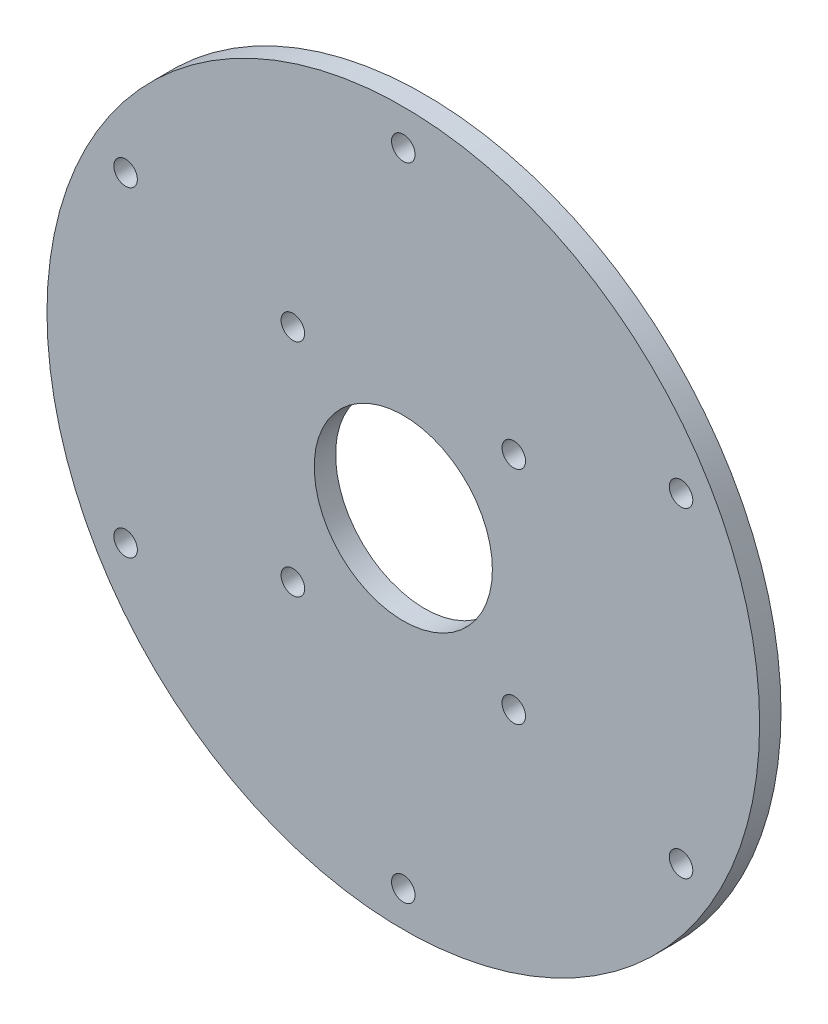
SolidWorks part; units mm, degrees
ref_plane "前视基准面" through (0, 0, 0) normal (0, 0, 1) x (1, 0, 0)
ref_plane "上视基准面" through (0, 0, 0) normal (0, 1, 0) x (1, 0, 0)
ref_plane "右视基准面" through (0, 0, 0) normal (1, 0, 0) x (0, 0, -1)
other "Configuration Table"
sketch "草图1" plane through (0, 0, 0) normal (0, 0, 1) x (1, 0, 0)
  line L0 (0, 0) -> (61.0193, 0) construction
  line L1 (0, 40) -> (0, -27.3482) construction
  line L2 (-38.9711, 22.5) -> (0, 0) construction
  circle A0 centre (0, 0) radius 50
  circle A1 centre (-15.5, 15.5) radius 1.65
  circle A2 centre (15.5, 15.5) radius 1.65
  circle A3 centre (15.5, -15.5) radius 1.65
  circle A4 centre (-15.5, -15.5) radius 1.65
  circle A5 centre (0, 0) radius 12.5
  circle A6 centre (-38.9711, 22.5) radius 1.65
  circle A12 centre (0, 45) radius 1.65
  circle A13 centre (38.9711, 22.5) radius 1.65
  circle A14 centre (38.9711, -22.5) radius 1.65
  circle A15 centre (0, -45) radius 1.65
  circle A16 centre (-38.9711, -22.5) radius 1.65
  point P18 (0, 0)
  point P31 (0, 0)
  point P32 (0, 0)
  dimension "D1" = 100
  dimension "D2" = 3.3
  dimension "D4" = 4
  dimension "D5" = 25
  dimension "D6" = 3.3
  dimension "D3" = 15.5
  dimension "D7" = 45
  dimension "D8" = 60
  dimension "D9" = 6
extrude "凸台-拉伸1" add sketch "草图1" along normal blind 3
